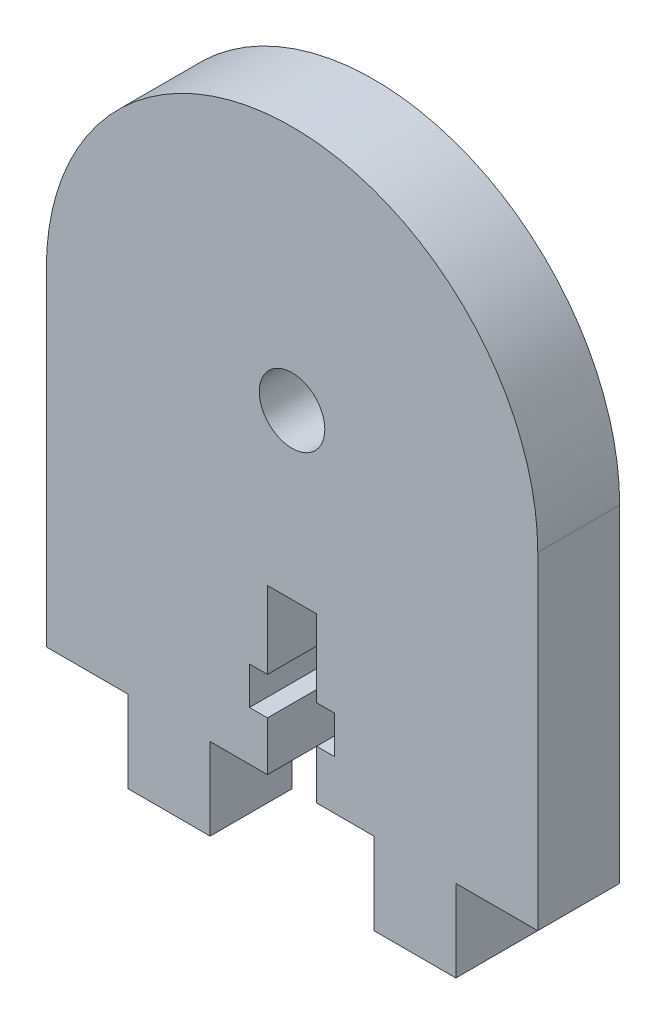
SolidWorks part; units mm, degrees
ref_plane "Front Plane" through (0, 0, 0) normal (0, 0, 1) x (1, 0, 0)
ref_plane "Top Plane" through (0, 0, 0) normal (0, 1, 0) x (1, 0, 0)
ref_plane "Right Plane" through (0, 0, 0) normal (1, 0, 0) x (0, 0, -1)
sketch "Sketch1" plane through (0, 0, 0) normal (0, 0, 1) x (1, 0, 0)
  line L0 (-10, 0) -> (-15, 0)
  line L1 (-15, 0) -> (-15, 20)
  line L2 (-15, 20) -> (15, 20) construction
  line L3 (15, 20) -> (15, 0)
  line L4 (15, 0) -> (10, 0)
  line L5 (0, 0) -> (0, 11.2208) construction
  line L6 (-1.5, 0) -> (-5, 0)
  line L7 (-5, -5) -> (-10, -5)
  line L8 (-10, -5) -> (-10, 0)
  line L9 (-5, -5) -> (-5, 0)
  line L10 (1.5, 0) -> (5, 0)
  line L11 (5, 0) -> (5, -5)
  line L12 (5, -5) -> (10, -5)
  line L13 (10, -5) -> (10, 0)
  line L14 (-1.5, 0) -> (1.5, 0) construction
  line L15 (1.5, 0) -> (1.5, 3)
  line L16 (1.5, 5.3) -> (2.6, 5.3)
  line L17 (-2.6, 3) -> (-2.6, 5.3)
  line L18 (2.6, 3) -> (1.5, 3)
  line L19 (1.5, 5.3) -> (1.5, 10)
  line L20 (1.5, 10) -> (-1.5, 10)
  line L21 (-1.5, 10) -> (-1.5, 5.3)
  line L22 (-1.5, 3) -> (-2.6, 3)
  line L23 (2.6, 5.3) -> (2.6, 3)
  line L24 (-2.6, 5.3) -> (-1.5, 5.3)
  line L25 (-1.5, 3) -> (-1.5, 0)
  line L26 (0, 10) -> (0, 0) construction
  arc A0 (-15, 20) -> (15, 20) centre (0, 20) cw
  circle A1 centre (0, 20) radius 2
  dimension "D3" = 4
  dimension "D1" = 5
  dimension "D2" = 20
  dimension "D4" = 10
  dimension "D5" = 5
  dimension "D6" = 5
  dimension "D7" = 5.2
  dimension "D8" = 3
  dimension "D9" = 2.3
  dimension "D10" = 3
  dimension "D11" = 10
extrude "Boss-Extrude1" add sketch "Sketch1" along normal blind 5
